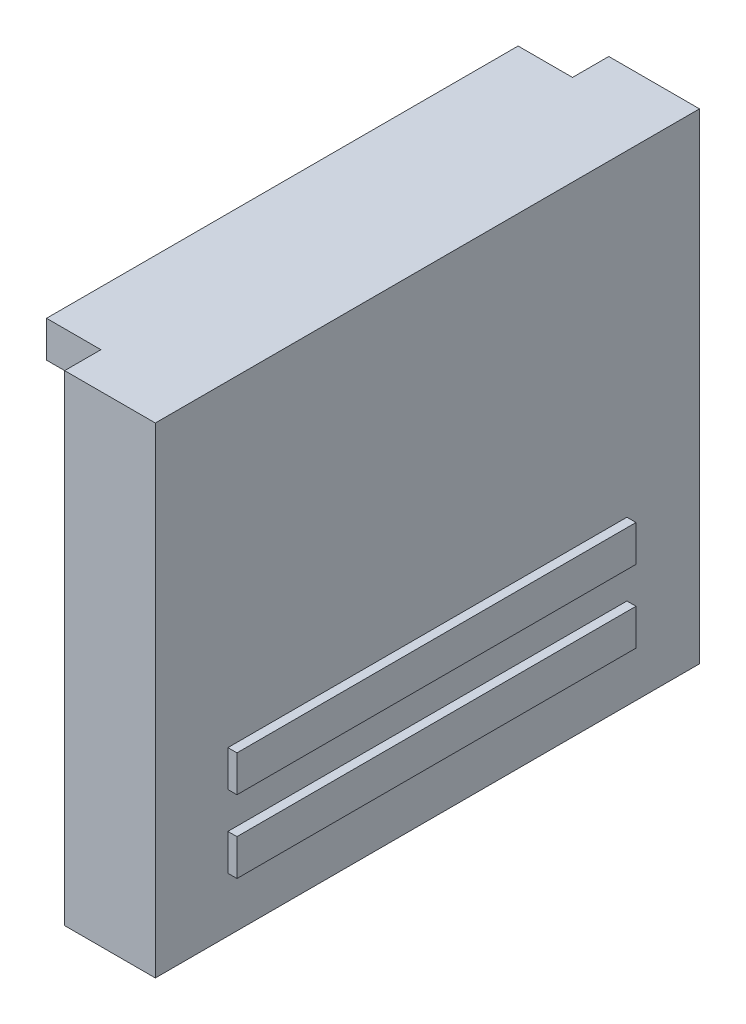
SolidWorks part; units mm, degrees
ref_plane "Front Plane" through (0, 0, 0) normal (0, 0, 1) x (1, 0, 0)
ref_plane "Top Plane" through (0, 0, 0) normal (0, 1, 0) x (1, 0, 0)
ref_plane "Right Plane" through (0, 0, 0) normal (1, 0, 0) x (0, 0, -1)
ref_plane "Plane1" through (179.1508, 0, 0) normal (1, 0, 0) x (0, 0, -1)
sketch "Sketch1" plane through (179.1508, 0, 0) normal (1, 0, 0) x (0, 0, -1)
  line L0 (-134, 37) -> (-134, 63.5)
  line L1 (-134, 63.5) -> (-164, 63.5)
  line L2 (-164, 63.5) -> (-164, 37)
  line L3 (-164, 37) -> (-134, 37)
extrude "Boss-Extrude1" add sketch "Sketch1" along normal mid plane 5
ref_plane "Plane2" through (181.6508, 0, 0) normal (1, 0, 0) x (0, 0, -1)
sketch "Sketch2" plane through (181.6508, 0, 0) normal (1, 0, 0) x (0, 0, -1)
  line L0 (-138, 40) -> (-138, 42)
  line L1 (-138, 42) -> (-160, 42)
  line L2 (-160, 42) -> (-160, 40)
  line L3 (-160, 40) -> (-138, 40)
  line L4 (-138, 44) -> (-138, 46)
  line L5 (-138, 46) -> (-160, 46)
  line L6 (-160, 46) -> (-160, 44)
  line L7 (-160, 44) -> (-138, 44)
extrude "Boss-Extrude2" add sketch "Sketch2" along normal mid plane 1
ref_plane "Plane3" through (175.1508, 0, 0) normal (1, 0, 0) x (0, 0, -1)
sketch "Sketch3" plane through (175.1508, 0, 0) normal (1, 0, 0) x (0, 0, -1)
  line L0 (-136, 61.5) -> (-136, 63.5)
  line L1 (-136, 63.5) -> (-162, 63.5)
  line L2 (-162, 63.5) -> (-162, 61.5)
  line L3 (-162, 61.5) -> (-136, 61.5)
extrude "Boss-Extrude3" add sketch "Sketch3" along normal mid plane 3
ref_plane "Plane4" through (174.1508, 0, 0) normal (1, 0, 0) x (0, 0, -1)
sketch "Sketch4" plane through (174.1508, 0, 0) normal (1, 0, 0) x (0, 0, -1)
  circle A0 centre (-149, 43) radius 2
extrude "Boss-Extrude4" add sketch "Sketch4" along normal mid plane 5
